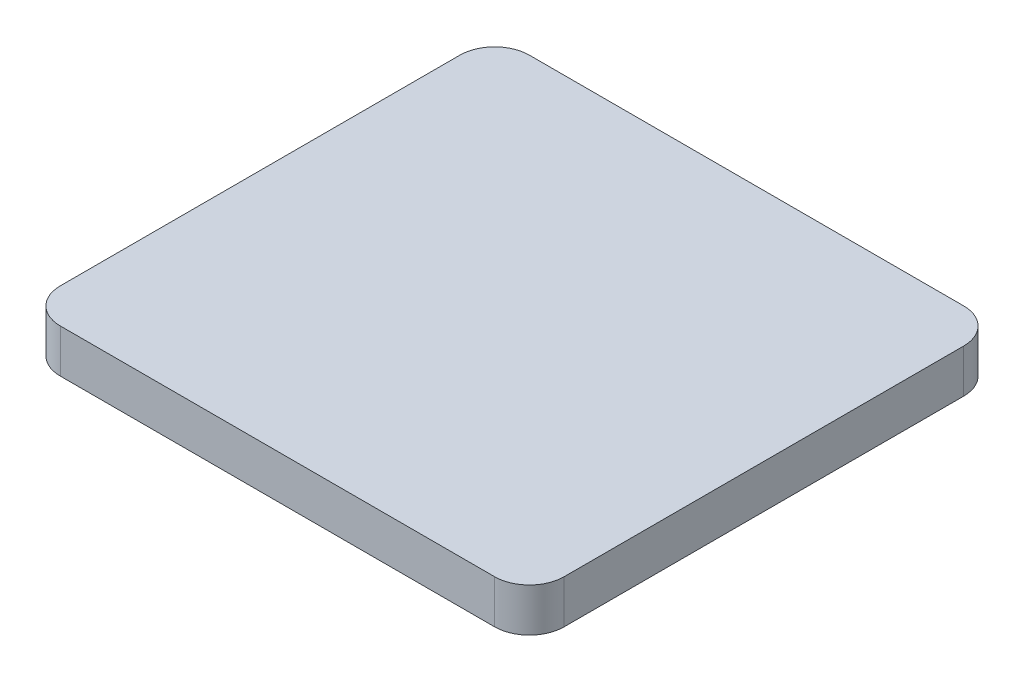
SolidWorks part; units mm, degrees
ref_plane "Front Plane" through (0, 0, 0) normal (0, 0, 1) x (1, 0, 0)
ref_plane "Top Plane" through (0, 0, 0) normal (0, 1, 0) x (1, 0, 0)
ref_plane "Right Plane" through (0, 0, 0) normal (1, 0, 0) x (0, 0, -1)
sketch "Sketch1" plane through (0, 0, 0) normal (0, 1, 0) x (1, 0, 0)
  line L4 (-125, 270) -> (125, 270)
  line L5 (-145, 250) -> (-145, 20)
  line L6 (-125, 0) -> (125, 0)
  line L7 (145, 250) -> (145, 20)
  arc A0 (-145, 20) -> (-125, 0) centre (-125, 20) ccw
  arc A1 (125, 0) -> (145, 20) centre (125, 20) ccw
  arc A2 (125, 270) -> (145, 250) centre (125, 250) cw
  arc A3 (-125, 270) -> (-145, 250) centre (-125, 250) ccw
  dimension "D2" = 20
  dimension "D1" = 250
  dimension "D3" = 230
extrude "Boss-Extrude1" add sketch "Sketch1" along normal blind 25
